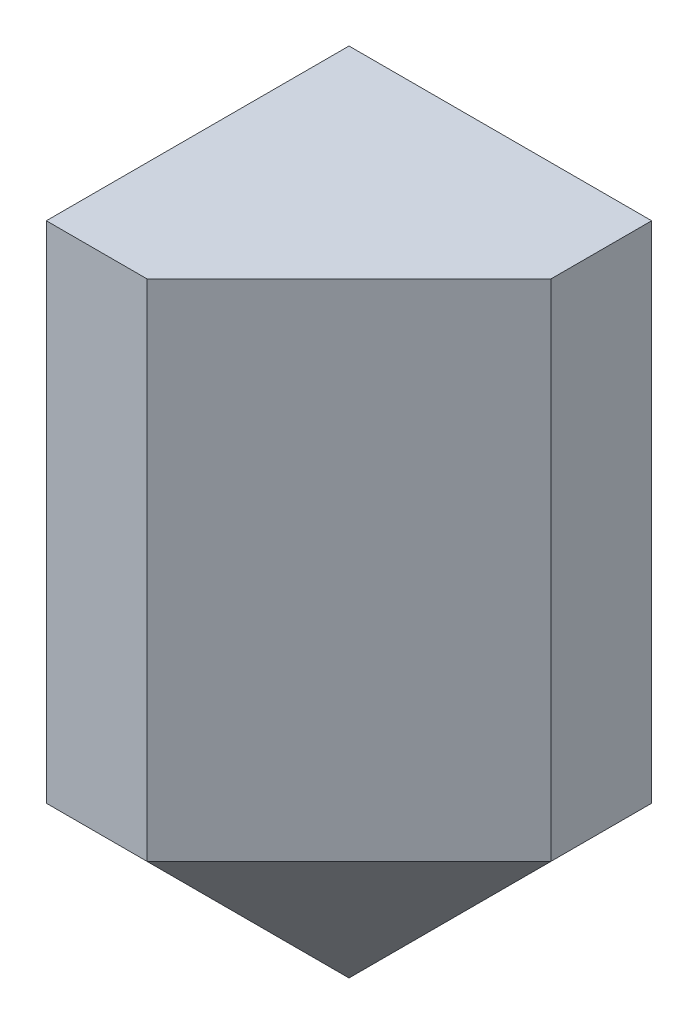
SolidWorks part; units mm, degrees
material "ABS"
ref_plane "Piano frontale" through (0, 0, 0) normal (0, 0, 1) x (1, 0, 0)
ref_plane "Piano superiore" through (0, 0, 0) normal (0, 1, 0) x (1, 0, 0)
ref_plane "Piano destro" through (0, 0, 0) normal (1, 0, 0) x (0, 0, -1)
sketch "Schizzo1" plane through (0, 0, 0) normal (0, 0, 1) x (1, 0, 0)
  line L1 (0, 0) -> (30, 0)
  line L2 (0, 0) -> (0, 40)
  line L3 (0, 40) -> (30, 40)
  line L4 (30, 0) -> (30, 40)
  dimension "D1" = 30
  dimension "D2" = 40
extrude "Estrusione-Estrusione1" add sketch "Schizzo1" along normal blind 30
chamfer "Smusso1" distance 20 angle 45 3 edges at (30, 20, 30) (30, 0, 15) (15, 0, 30)
sketch "Schizzo2" plane through (0, 40, 0) normal (0, 1, 0) x (1, 0, 0)
  line L0 (0, 0) -> (30, 0)
  line L1 (30, 0) -> (30, -10)
  line L2 (30, -10) -> (10, -30)
  line L3 (10, -30) -> (0, -30)
  line L4 (0, -30) -> (0, 0)
extrude "Estrusione-Estrusione2" add sketch "Schizzo2" along normal blind 30
hole_wizard "Foro per Vite M5-1" positions "Schizzo3" profile "Schizzo4" hole size "M5" standard "ISO"
sketch "Schizzo3" plane through (0, 0, 0) normal (-1, 0, 0) x (0, 0, 1)
  line L4 (0, 70) -> (30, 70) construction
  line L5 (0, 70) -> (0, 0) construction
  point P0 (18, 20)
  dimension "D1" = 18
  dimension "D2" = 50
sketch "Schizzo4" plane through (0, 20, 18) normal (0, 1, 0) x (0, 0, 1)
  line L0 (0, 0) -> (0, 14.6524)
  line L1 (0, 14.6524) -> (2.75, 13)
  line L2 (2.75, 13) -> (2.75, 0)
  line L5 (2.75, 0) -> (0, 0)
  line L10 (0, 14.6524) -> (-2.75, 13) construction
  line L11 (0, -6.35) -> (0, 107.95) construction
  dimension "Hole Dia." = 5.5
  dimension "Hole Depth" = 13
  dimension "Drill Angle" = 118
hole_wizard "Foro per Vite M5-2" positions "Schizzo3D1" profile "Schizzo5" hole size "M5" standard "ISO"
sketch3d "Schizzo3D1"
  line L0 (14, 20, 0) -> (14, 34, 0) construction
  line L2 (0, 70, 0) -> (0, 0, 0) construction
  line L4 (14, 48, 0) -> (14, 34, 0) construction
  line L5 (30, 70, 0) -> (0, 70, 0) construction
  point P21 (14, 48, 0)
  point P37 (14, 20, 0)
  point P42 (13.8941, 20, 0)
  point P43 (11.5459, 20, 0)
  point P44 (14, 20, 0)
  dimension "D1" = 14
  dimension "D2" = 14
  dimension "D3" = 22
  dimension "D4" = 14
sketch "Schizzo5" plane through (14, 20, 0) normal (1, 0, 0) x (0, 1, 0)
  line L0 (0, 0) -> (0, 14.6524)
  line L1 (0, 14.6524) -> (2.75, 13)
  line L2 (2.75, 13) -> (2.75, 0)
  line L5 (2.75, 0) -> (0, 0)
  line L10 (0, 14.6524) -> (-2.75, 13) construction
  line L11 (0, -6.35) -> (0, 107.95) construction
  dimension "Hole Dia." = 5.5
  dimension "Hole Depth" = 13
  dimension "Drill Angle" = 118
sketch "Schizzo6" plane through (0, 0, 0) normal (-1, 0, 0) x (0, 0, 1)
  line L0 (0, 70) -> (30, 70) construction
  line L1 (30, 70) -> (30, 20) construction
  circle A0 centre (15, 55) radius 7.5
  dimension "D1" = 15
  dimension "D2" = 15
  dimension "D3" = 15
extrude "Taglio-Estrusione1" cut sketch "Schizzo6" against normal blind 3
sketch "Schizzo7" plane through (3, 0, 0) normal (-1, 0, 0) x (0, 0, 1)
  point P0 (15, 55)
hole_wizard "Foro per Vite M4-1" positions "Schizzo7" profile "Schizzo8" hole size "M4" standard "ISO"
sketch "Schizzo8" plane through (3, 55, 15) normal (0, 1, 0) x (0, 0, 1)
  line L0 (0, 0) -> (0, 11.3219)
  line L1 (0, 11.3219) -> (2.2, 10)
  line L2 (2.2, 10) -> (2.2, 0)
  line L5 (2.2, 0) -> (0, 0)
  line L10 (0, 11.3219) -> (-2.2, 10) construction
  line L11 (0, -6.35) -> (0, 107.95) construction
  dimension "Hole Dia." = 4.4
  dimension "Hole Depth" = 10
  dimension "Drill Angle" = 118
